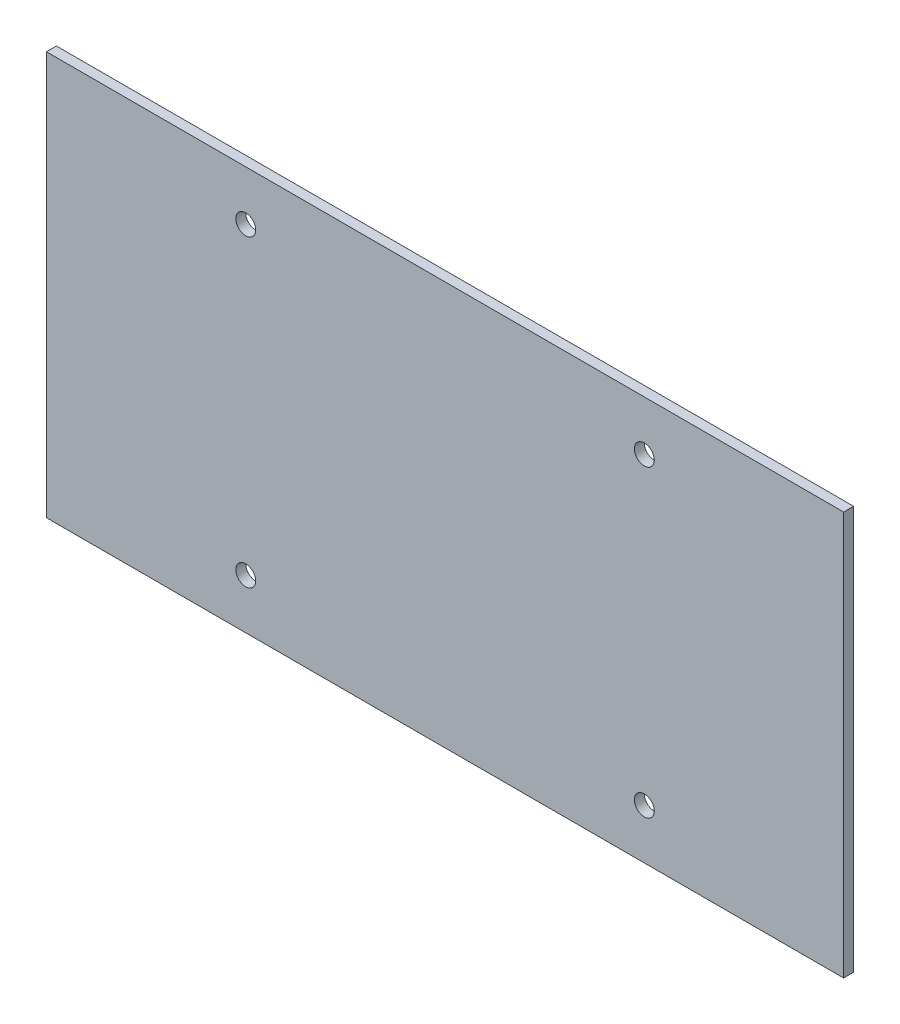
SolidWorks part; units mm, degrees
ref_plane "Ön Düzlem" through (0, 0, 0) normal (0, 0, 1) x (1, 0, 0)
ref_plane "Üst Düzlem" through (0, 0, 0) normal (0, 1, 0) x (1, 0, 0)
ref_plane "Sağ Düzlem" through (0, 0, 0) normal (1, 0, 0) x (0, 0, -1)
sketch "Çizim1" plane through (0, 0, 0) normal (0, 0, 1) x (1, 0, 0)
  line L0 (40, 81) -> (40, 0) construction
  line L1 (0, 0) -> (160, 0)
  line L2 (0, 0) -> (0, 81)
  line L3 (0, 81) -> (160, 81)
  line L4 (160, 0) -> (160, 81)
  line L5 (120, 81) -> (120, 0) construction
  line L6 (0, 71) -> (160, 71) construction
  line L7 (0, 10) -> (160, 10) construction
  circle A0 centre (40, 71) radius 2
  circle A1 centre (120, 71) radius 2
  circle A2 centre (40, 10) radius 2
  circle A3 centre (120, 10) radius 2
  dimension "D6" = 10
  dimension "D8" = 4
  dimension "D1" = 40
  dimension "D2" = 40
  dimension "D3" = 10
  dimension "D4" = 10
  dimension "D5" = 81
  dimension "D7" = 160
extrude "Yükseklik-Ekstrüzyon1" add sketch "Çizim1" along normal blind 2
